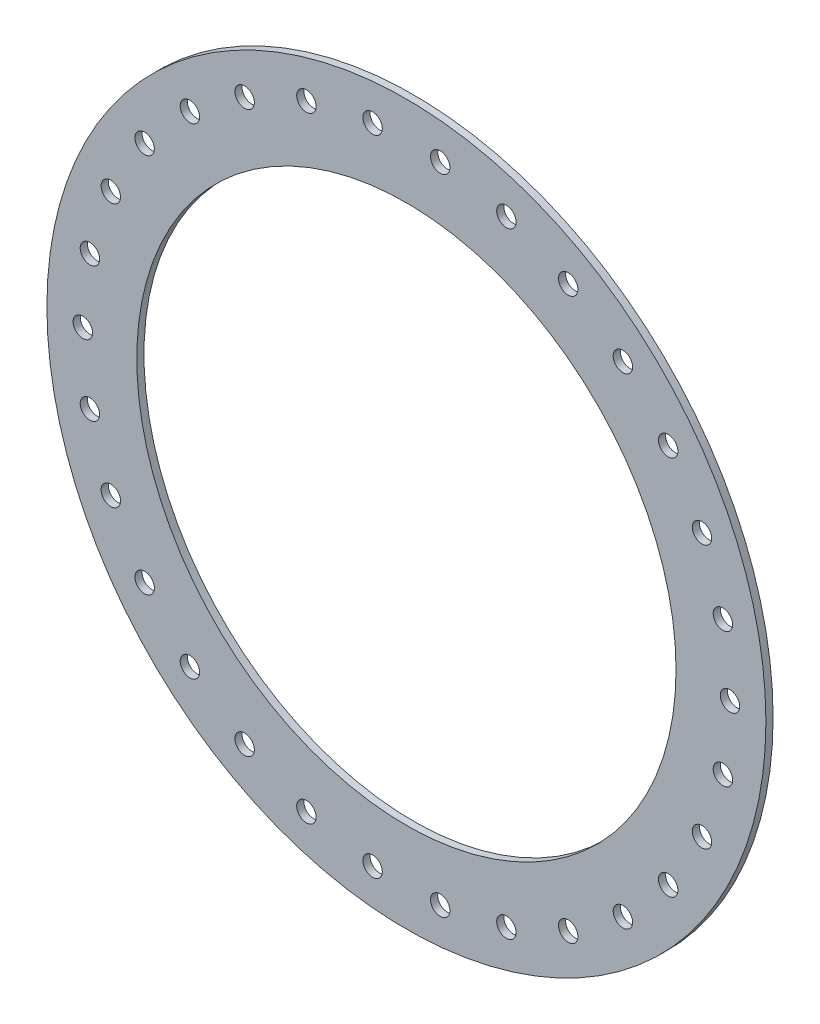
SolidWorks part; units mm, degrees
ref_plane "Alzado" through (0, 0, 0) normal (0, 0, 1) x (1, 0, 0)
ref_plane "Planta" through (0, 0, 0) normal (0, 1, 0) x (1, 0, 0)
ref_plane "Vista lateral" through (0, 0, 0) normal (1, 0, 0) x (0, 0, -1)
sketch "Croquis1" plane through (0, 0, 0) normal (0, 0, 1) x (1, 0, 0)
  circle A0 centre (0, 0) radius 200
  circle A1 centre (0, 0) radius 150
  circle A3 centre (145.6231, 105.8013) radius 5.4
  circle A4 centre (164.4382, 73.2126) radius 5.4
  circle A5 centre (176.0666, 37.4241) radius 5.4
  circle A6 centre (180, 0) radius 5.4
  circle A7 centre (176.0666, -37.4241) radius 5.4
  circle A8 centre (164.4382, -73.2126) radius 5.4
  circle A9 centre (145.6231, -105.8013) radius 5.4
  circle A10 centre (120.4435, -133.7661) radius 5.4
  circle A11 centre (90, -155.8846) radius 5.4
  circle A12 centre (55.6231, -171.1902) radius 5.4
  circle A13 centre (18.8151, -179.0139) radius 5.4
  circle A14 centre (-18.8151, -179.0139) radius 5.4
  circle A15 centre (-55.6231, -171.1902) radius 5.4
  circle A16 centre (-90, -155.8846) radius 5.4
  circle A17 centre (-120.4435, -133.7661) radius 5.4
  circle A18 centre (-145.6231, -105.8013) radius 5.4
  circle A19 centre (-164.4382, -73.2126) radius 5.4
  circle A20 centre (-176.0666, -37.4241) radius 5.4
  circle A21 centre (-180, 0) radius 5.4
  circle A22 centre (-176.0666, 37.4241) radius 5.4
  circle A23 centre (-164.4382, 73.2126) radius 5.4
  circle A24 centre (-145.6231, 105.8013) radius 5.4
  circle A25 centre (-120.4435, 133.7661) radius 5.4
  circle A26 centre (-90, 155.8846) radius 5.4
  circle A27 centre (-55.6231, 171.1902) radius 5.4
  circle A28 centre (-18.8151, 179.0139) radius 5.4
  circle A29 centre (18.8151, 179.0139) radius 5.4
  circle A30 centre (55.6231, 171.1902) radius 5.4
  circle A31 centre (90, 155.8846) radius 5.4
  circle A32 centre (120.4435, 133.7661) radius 5.4
extrude "Saliente-Extruir1" add sketch "Croquis1" along normal blind 4
